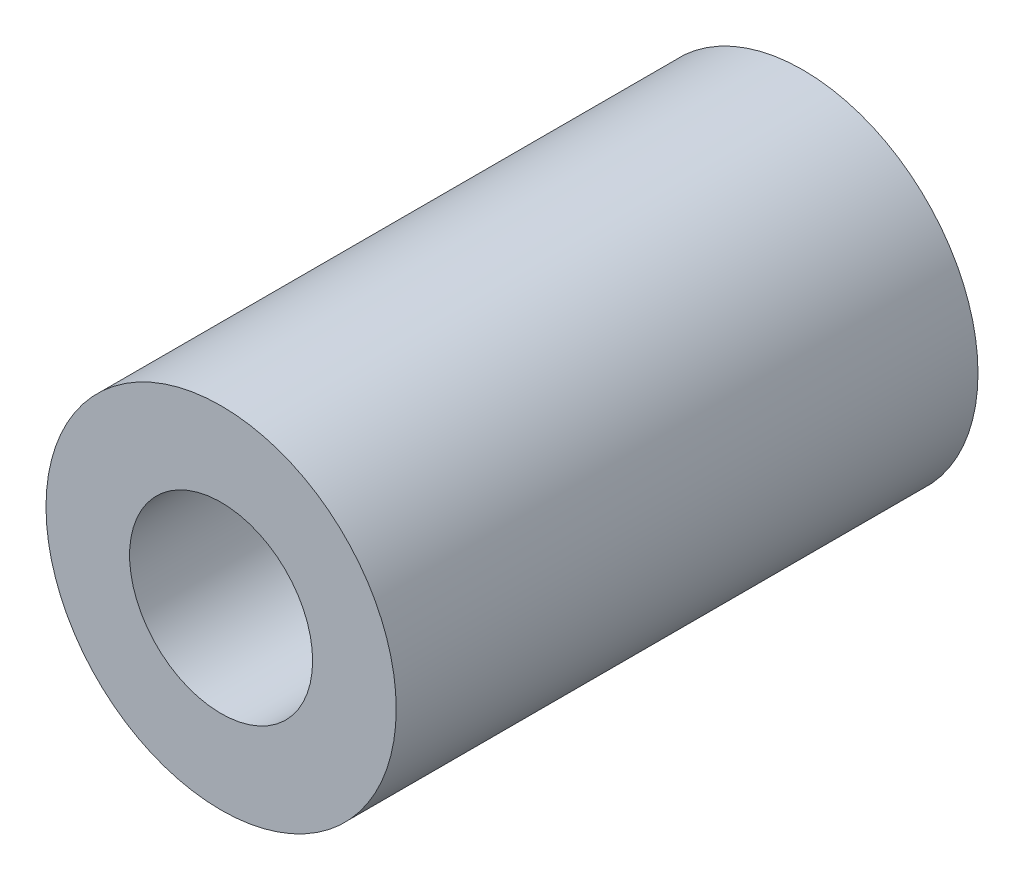
SolidWorks part; units mm, degrees
ref_plane "Front Plane" through (0, 0, 0) normal (0, 0, 1) x (1, 0, 0)
ref_plane "Top Plane" through (0, 0, 0) normal (0, 1, 0) x (1, 0, 0)
ref_plane "Right Plane" through (0, 0, 0) normal (1, 0, 0) x (0, 0, -1)
sketch "Sketch1" plane through (0, 0, 0) normal (0, 0, 1) x (1, 0, 0)
  circle A0 centre (0, 0) radius 2.4892
  circle A1 centre (0, 0) radius 4.7625
  dimension "D1" = 4.9784
  dimension "D2" = 9.525
extrude "Boss-Extrude1" add sketch "Sketch1" along normal mid plane 15.8242
